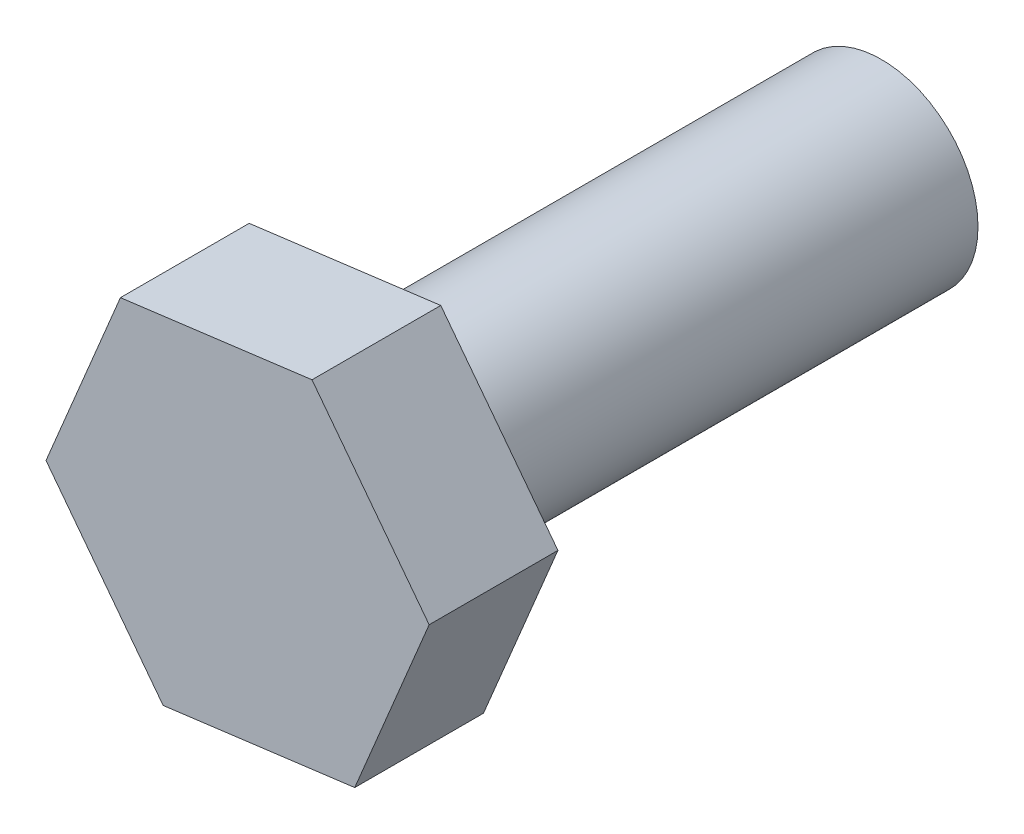
SolidWorks part; units mm, degrees
ref_plane "Front Plane" through (0, 0, 0) normal (0, 0, 1) x (1, 0, 0)
ref_plane "Top Plane" through (0, 0, 0) normal (0, 1, 0) x (1, 0, 0)
ref_plane "Right Plane" through (0, 0, 0) normal (1, 0, 0) x (0, 0, -1)
sketch "Sketch1" plane through (0, 0, 0) normal (0, 0, 1) x (1, 0, 0)
  circle A0 centre (0, 0) radius 2.3813
  dimension "D1" = 4.7625
extrude "Extrude1" add sketch "Sketch1" against normal blind 12.7
sketch "Sketch2" plane through (0, 0, 0) normal (0, 0, 1) x (1, 0, 0)
  line L1 (1.8351, 4.3948) -> (-2.8884, 3.7866)
  line L2 (-2.8884, 3.7866) -> (-4.7235, -0.6081)
  line L3 (-4.7235, -0.6081) -> (-1.8351, -4.3948)
  line L4 (-1.8351, -4.3948) -> (2.8884, -3.7866)
  line L5 (2.8884, -3.7866) -> (4.7235, 0.6081)
  line L6 (4.7235, 0.6081) -> (1.8351, 4.3948)
extrude "Extrude2" add sketch "Sketch2" along normal blind 3.175
